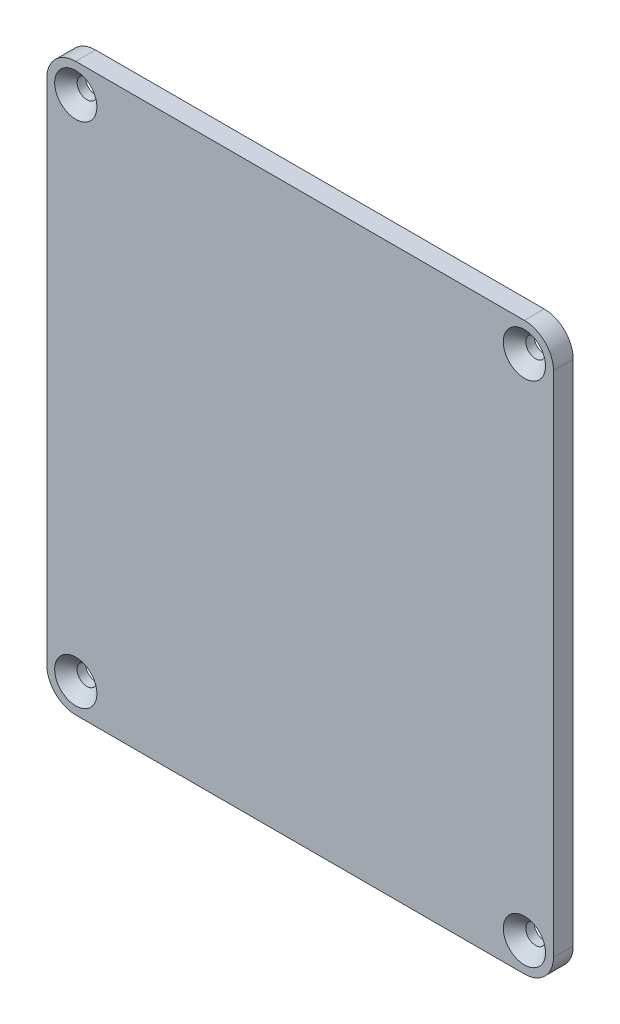
SolidWorks part; units mm, degrees
ref_plane "Спереди" through (0, 0, 0) normal (0, 0, 1) x (1, 0, 0)
ref_plane "Сверху" through (0, 0, 0) normal (0, 1, 0) x (1, 0, 0)
ref_plane "Справа" through (0, 0, 0) normal (1, 0, 0) x (0, 0, -1)
sketch "Эскиз1" plane through (0, 0, 0) normal (0, 0, 1) x (1, 0, 0)
  line L5 (0, 0) -> (50000, 0) construction
  line L6 (0, 0) -> (0, 50000) construction
  line L9 (38.4, -38.5) -> (38.4, 38.5)
  line L10 (34, 42.9) -> (-34, 42.9)
  line L11 (-38.4, 38.5) -> (-38.4, -38.5)
  line L12 (-34, -42.9) -> (34, -42.9)
  line L13 (38.4, -38.5) -> (38.4, 38.5)
  line L14 (34, 42.9) -> (-34, 42.9)
  line L15 (-38.4, 38.5) -> (-38.4, -38.5)
  line L16 (-34, -42.9) -> (34, -42.9)
  circle A4 centre (34, -38.5) radius 1.5
  circle A5 centre (-34, -38.5) radius 1.5
  circle A6 centre (34, 38.5) radius 1.5
  circle A7 centre (-34, 38.5) radius 1.5
  arc A8 (34, -42.9) -> (38.4, -38.5) centre (34, -38.5) ccw
  arc A9 (38.4, 38.5) -> (34, 42.9) centre (34, 38.5) ccw
  arc A10 (-34, 42.9) -> (-38.4, 38.5) centre (-34, 38.5) ccw
  arc A11 (-38.4, -38.5) -> (-34, -42.9) centre (-34, -38.5) ccw
  arc A12 (34, -42.9) -> (38.4, -38.5) centre (34, -38.5) ccw
  arc A13 (38.4, 38.5) -> (34, 42.9) centre (34, 38.5) ccw
  arc A14 (-34, 42.9) -> (-38.4, 38.5) centre (-34, 38.5) ccw
  arc A15 (-38.4, -38.5) -> (-34, -42.9) centre (-34, -38.5) ccw
  dimension "D2" = 3
  dimension "D1" = 0.1
extrude "Бобышка-Вытянуть1" add sketch "Эскиз1" along normal blind 3
chamfer "Фаска1" distance 1.7 angle 45 4 edges at (35.5, -38.5, 3) (32.5, 38.5, 3) (-32.5, 38.5, 3) (-35.5, -38.5, 3)
